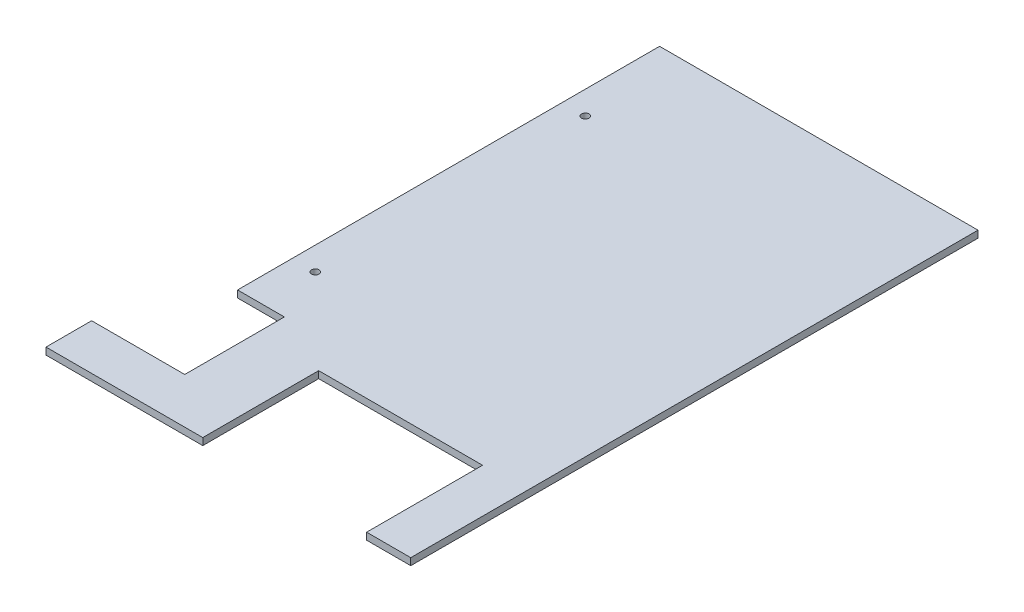
SolidWorks part; units mm, degrees
ref_plane "Front Plane" through (0, 0, 0) normal (0, 0, 1) x (1, 0, 0)
ref_plane "Top Plane" through (0, 0, 0) normal (0, 1, 0) x (1, 0, 0)
ref_plane "Right Plane" through (0, 0, 0) normal (1, 0, 0) x (0, 0, -1)
sketch "Sketch1" plane through (0, -561.2989, 0) normal (0, -1, 0) x (1, 0, 0)
  line L1 (-11.1108, 789.4201) -> (16.2392, 789.4201)
  line L2 (-31.2108, 727.0201) -> (-31.2108, 545.7201)
  line L3 (-31.2108, 545.7201) -> (105.5892, 545.7201)
  line L4 (105.5892, 789.4201) -> (105.5892, 545.7201)
  line L5 (104.7892, 545.6201) -> (-11.2108, 545.6201) construction
  line L7 (-31.2108, 727.0201) -> (-11.1108, 727.0201)
  line L8 (-11.1108, 727.0201) -> (-11.1108, 789.4201)
  line L9 (86.6392, 789.4201) -> (105.5892, 789.4201)
  line L11 (16.2392, 789.4201) -> (16.2392, 739.6201)
  line L12 (16.2392, 739.6201) -> (86.6392, 739.6201)
  line L13 (86.6392, 789.4201) -> (86.6392, 739.6201)
  line L16 (86.4392, 739.8201) -> (16.4392, 739.8201) construction
  line L18 (-2.7108, 732.2486) -> (-2.7108, 764.9917) construction
  line L19 (-3.2108, 769.6201) -> (-14.7108, 769.6201) construction
  line L20 (-31.4108, 525.4201) -> (-31.4108, 727.0201) construction
  line L21 (-31.4108, 727.0201) -> (-87.7108, 727.0201) construction
  circle A0 centre (-21.2108, 703.6201) radius 1.6
  circle A2 centre (-21.2108, 587.6201) radius 1.6
  circle A3 centre (-21.2108, 645.6201) radius 1.6 [skipped]
  dimension "D10" = 3
  dimension "D1" = 0.1
  dimension "D4" = 0.2
  dimension "D6" = 8.4
  dimension "D7" = 19.8
  dimension "D8" = 0.2
  dimension "D9" = 180
extrude "Boss-Extrude1" add sketch "Sketch1" along normal blind 3
sketch "Sketch2" plane through (-11.1108, 0, 0) normal (-1, 0, 0) x (0, 0, 1)
  line L0 (789.4201, -561.2989) -> (727.0201, -561.2989) construction
  line L1 (789.4201, -564.2989) -> (769.8201, -564.2989)
  line L2 (789.4201, -564.2989) -> (789.4201, -561.2989)
  line L3 (789.4201, -561.2989) -> (769.8201, -561.2989)
  line L4 (769.8201, -564.2989) -> (769.8201, -561.2989)
  dimension "D1" = 19.6
extrude "Boss-Extrude2" add sketch "Sketch2" along normal blind 40
